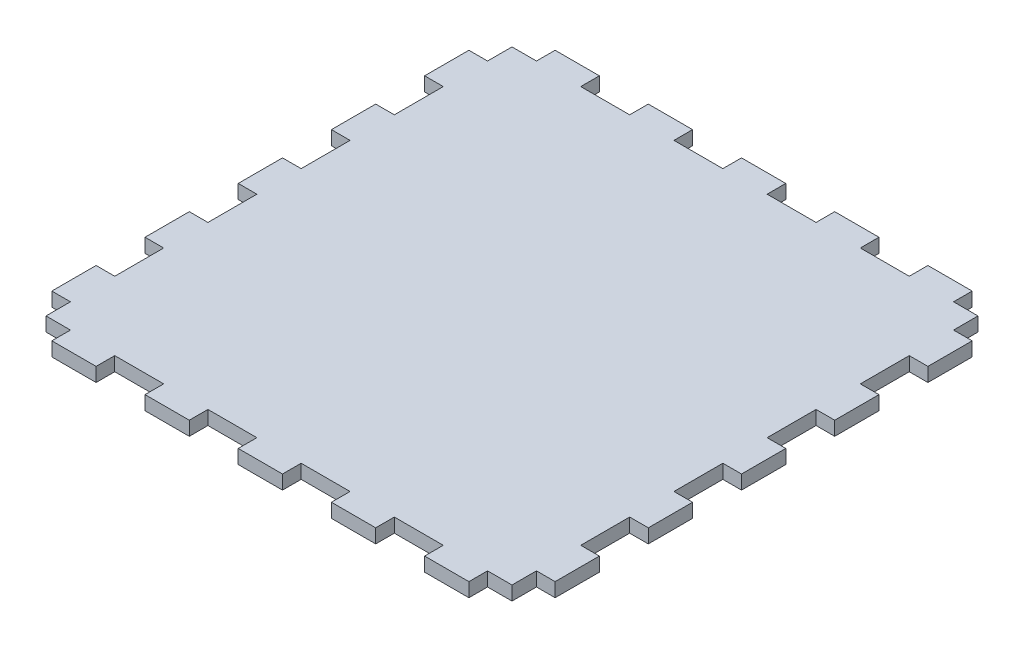
SolidWorks part; units mm, degrees
material "Teak"
ref_plane "Front Plane" through (0, 0, 0) normal (0, 0, 1) x (1, 0, 0)
ref_plane "Top Plane" through (0, 0, 0) normal (0, 1, 0) x (1, 0, 0)
ref_plane "Right Plane" through (0, 0, 0) normal (1, 0, 0) x (0, 0, -1)
sketch "Sketch2" plane through (0, 0, 0) normal (0, 1, 0) x (1, 0, 0)
  line L1 (-50, -50) -> (50, -50)
  line L2 (-50, -50) -> (-50, 50)
  line L3 (-50, 50) -> (50, 50)
  line L4 (50, -50) -> (50, 50)
  line L5 (-50, -50) -> (50, 50) construction
  line L6 (-50, 50) -> (50, -50) construction
  point P0 (0, 0)
  dimension "D1" = 100
  dimension "D2" = 100
extrude "Boss-Extrude1" add sketch "Sketch2" along normal blind 3
sketch "Sketch4" plane through (0, 0, 50) normal (0, 0, 1) x (1, 0, 0)
  line L0 (50, 1.5) -> (45, 1.5) construction
  line L1 (50, 3) -> (50, 0) construction
  line L2 (45, 1.5) -> (-45, 1.5) construction
  line L3 (-45, 1.5) -> (-50, 1.5) construction
  line L4 (-50, 3) -> (-50, 0) construction
  line L5 (-50, 3) -> (50, 3) construction
  line L6 (-35.25, 0) -> (-44.75, 0)
  line L7 (-35.25, 0) -> (-35.25, 3)
  line L8 (-35.25, 3) -> (-44.75, 3)
  line L9 (-44.75, 0) -> (-44.75, 3)
  line L10 (-35.25, 0) -> (-44.75, 3) construction
  line L11 (-35.25, 3) -> (-44.75, 0) construction
  line L12 (-25.25, 0) -> (-25.25, 3)
  line L13 (-25.25, 0) -> (-34.75, 0)
  line L14 (-34.75, 0) -> (-34.75, 3)
  line L15 (-25.25, 3) -> (-34.75, 3)
  line L16 (-15.25, 0) -> (-15.25, 3)
  line L17 (-15.25, 0) -> (-24.75, 0)
  line L18 (-24.75, 0) -> (-24.75, 3)
  line L19 (-15.25, 3) -> (-24.75, 3)
  line L20 (-5.25, 0) -> (-5.25, 3)
  line L21 (-5.25, 0) -> (-14.75, 0)
  line L22 (-14.75, 0) -> (-14.75, 3)
  line L23 (-5.25, 3) -> (-14.75, 3)
  line L24 (4.75, 0) -> (4.75, 3)
  line L25 (4.75, 0) -> (-4.75, 0)
  line L26 (-4.75, 0) -> (-4.75, 3)
  line L27 (4.75, 3) -> (-4.75, 3)
  line L28 (-35.25, 0) -> (-25.25, 0) construction
  line L29 (-15.25, 0) -> (-15.25, 3)
  line L30 (-15.25, 0) -> (-24.75, 0)
  line L31 (-24.75, 0) -> (-24.75, 3)
  line L32 (-15.25, 3) -> (-24.75, 3)
  line L33 (4.75, 0) -> (4.75, 3)
  line L34 (4.75, 0) -> (-4.75, 0)
  line L35 (-4.75, 0) -> (-4.75, 3)
  line L36 (4.75, 3) -> (-4.75, 3)
  line L37 (24.75, 0) -> (24.75, 3)
  line L38 (24.75, 0) -> (15.25, 0)
  line L39 (15.25, 0) -> (15.25, 3)
  line L40 (24.75, 3) -> (15.25, 3)
  line L41 (44.75, 0) -> (44.75, 3)
  line L42 (44.75, 0) -> (35.25, 0)
  line L43 (35.25, 0) -> (35.25, 3)
  line L44 (44.75, 3) -> (35.25, 3)
  line L45 (-35.25, 0) -> (-15.25, 0) construction
  point P8 (-40, 1.5)
  point P15 (0, 0)
  point P16 (-52.4687, 43.8595)
  point P53 (0, 0)
  line M6 (-50, 0) -> (50, 0)
  line M8 (50, 3) -> (-50, 3)
  dimension "D1" = 4.75
  dimension "D3" = 5
  dimension "D5" = 10
  dimension "D7" = 20
  dimension "D8" = 5
  dimension "D4" = 5
  dimension "D6" = 5
extrude "Boss-Extrude2" add sketch "Sketch4" along normal blind 4 contours L9 L7 M6 M8 | L16 L12 M6 M8 | L24 L20 M6 M8 | L39 L37 M6 M8 | L43 L41 M6 M8
sketch "Sketch5" plane through (-50, 0, 0) normal (-1, 0, 0) x (0, 0, 1)
  line L0 (50, 0) -> (50, 3) construction
  line L1 (54, 1.5) -> (50, 1.5) construction
  line L2 (54, 0) -> (54, 3) construction
  line L3 (50, 1.5) -> (-45, 1.5) construction
  line L4 (-45, 1.5) -> (-50, 1.5) construction
  line L5 (-50, 3) -> (-50, 0) construction
  line L6 (-50, 3) -> (50, 3) construction
  line L7 (-35.25, 0) -> (-44.75, 0)
  line L8 (-35.25, 0) -> (-35.25, 3)
  line L9 (-35.25, 3) -> (-44.75, 3)
  line L10 (-44.75, 0) -> (-44.75, 3)
  line L11 (-35.25, 0) -> (-44.75, 3) construction
  line L12 (-35.25, 3) -> (-44.75, 0) construction
  line L13 (-15.25, 0) -> (-15.25, 3)
  line L14 (-15.25, 0) -> (-24.75, 0)
  line L15 (-24.75, 0) -> (-24.75, 3)
  line L16 (-15.25, 3) -> (-24.75, 3)
  line L17 (-35.25, 0) -> (-15.25, 0) construction
  line L18 (-15.25, 0) -> (-15.25, 3)
  line L19 (-15.25, 0) -> (-24.75, 0)
  line L20 (-24.75, 0) -> (-24.75, 3)
  line L21 (-15.25, 3) -> (-24.75, 3)
  line L22 (4.75, 0) -> (4.75, 3)
  line L23 (4.75, 0) -> (-4.75, 0)
  line L24 (-4.75, 0) -> (-4.75, 3)
  line L25 (4.75, 3) -> (-4.75, 3)
  line L26 (24.75, 0) -> (24.75, 3)
  line L27 (24.75, 0) -> (15.25, 0)
  line L28 (15.25, 0) -> (15.25, 3)
  line L29 (24.75, 3) -> (15.25, 3)
  line L30 (44.75, 0) -> (44.75, 3)
  line L31 (44.75, 0) -> (35.25, 0)
  line L32 (35.25, 0) -> (35.25, 3)
  line L33 (44.75, 3) -> (35.25, 3)
  line L34 (-35.25, 0) -> (-15.25, 0) construction
  point P7 (-40, 1.5)
  dimension "D1" = 5
  dimension "D2" = 9.5
  dimension "D3" = 5
  dimension "D5" = 20
  dimension "D7" = 20
  dimension "D4" = 2
  dimension "D6" = 5
extrude "Boss-Extrude3" add sketch "Sketch5" along normal blind 4 contours L9 L10 L7 L8 | L14 L15 L16 L13 | L23 L24 L25 L22 | L27 L28 L29 L26 | L31 L32 L33 L30
sketch "Sketch6" plane through (50, 0, 0) normal (1, 0, 0) x (0, 0, -1)
  line L1 (45, 1.5) -> (-45, 1.5) construction
  line L3 (-45, 1.5) -> (-50, 1.5) construction
  line L4 (45, 1.5) -> (50, 1.5) construction
  line L5 (50, 3) -> (50, 0) construction
  line L7 (-50, 3) -> (-50, 0) construction
  line L8 (-50, 3) -> (50, 3) construction
  line L9 (-35.25, 0) -> (-44.75, 0)
  line L10 (-35.25, 0) -> (-35.25, 3)
  line L11 (-35.25, 3) -> (-44.75, 3)
  line L12 (-44.75, 0) -> (-44.75, 3)
  line L13 (-35.25, 0) -> (-44.75, 3) construction
  line L14 (-35.25, 3) -> (-44.75, 0) construction
  line L15 (-15.25, 0) -> (-15.25, 3)
  line L16 (-15.25, 0) -> (-24.75, 0)
  line L17 (-24.75, 0) -> (-24.75, 3)
  line L18 (-15.25, 3) -> (-24.75, 3)
  line L19 (4.75, 0) -> (4.75, 3)
  line L20 (4.75, 0) -> (-4.75, 0)
  line L21 (-4.75, 0) -> (-4.75, 3)
  line L22 (4.75, 3) -> (-4.75, 3)
  line L23 (24.75, 0) -> (24.75, 3)
  line L24 (24.75, 0) -> (15.25, 0)
  line L25 (15.25, 0) -> (15.25, 3)
  line L26 (24.75, 3) -> (15.25, 3)
  line L27 (44.75, 0) -> (44.75, 3)
  line L28 (44.75, 0) -> (35.25, 0)
  line L29 (35.25, 0) -> (35.25, 3)
  line L30 (44.75, 3) -> (35.25, 3)
  line L31 (-35.25, 0) -> (-15.25, 0) construction
  point P0 (-40, 1.5)
  dimension "D1" = 5
  dimension "D2" = 5
  dimension "D3" = 9.5
  dimension "D4" = 5
  dimension "D6" = 20
  dimension "D5" = 5
extrude "Boss-Extrude4" add sketch "Sketch6" along normal blind 4 contours L10 L9 L12 L11 | L15 L18 L17 L16 | L19 L22 L21 L20 | L23 L26 L25 L24 | L27 L30 L29 L28
sketch "Sketch7" plane through (0, 0, -50) normal (0, 0, -1) x (-1, 0, 0)
  line L0 (-50, 1.5) -> (-45, 1.5) construction
  line L1 (-50, 3) -> (-50, 0) construction
  line L2 (-45, 1.5) -> (45, 1.5) construction
  line L3 (45, 1.5) -> (50, 1.5) construction
  line L4 (50, 0) -> (50, 3) construction
  line L5 (-50, 3) -> (50, 3) construction
  line L6 (-35.25, 0) -> (-44.75, 0)
  line L7 (-35.25, 0) -> (-35.25, 3)
  line L8 (-35.25, 3) -> (-44.75, 3)
  line L9 (-44.75, 0) -> (-44.75, 3)
  line L10 (-35.25, 0) -> (-44.75, 3) construction
  line L11 (-35.25, 3) -> (-44.75, 0) construction
  line L12 (-15.25, 0) -> (-15.25, 3)
  line L13 (-15.25, 0) -> (-24.75, 0)
  line L14 (-24.75, 0) -> (-24.75, 3)
  line L15 (-15.25, 3) -> (-24.75, 3)
  line L16 (4.75, 0) -> (4.75, 3)
  line L17 (4.75, 0) -> (-4.75, 0)
  line L18 (-4.75, 0) -> (-4.75, 3)
  line L19 (4.75, 3) -> (-4.75, 3)
  line L20 (24.75, 0) -> (24.75, 3)
  line L21 (24.75, 0) -> (15.25, 0)
  line L22 (15.25, 0) -> (15.25, 3)
  line L23 (24.75, 3) -> (15.25, 3)
  line L24 (44.75, 0) -> (44.75, 3)
  line L25 (44.75, 0) -> (35.25, 0)
  line L26 (35.25, 0) -> (35.25, 3)
  line L27 (44.75, 3) -> (35.25, 3)
  line L28 (-35.25, 0) -> (-15.25, 0) construction
  point P5 (-40, 1.5)
  dimension "D1" = 5
  dimension "D2" = 90
  dimension "D3" = 9.5
  dimension "D4" = 5
  dimension "D6" = 20
  dimension "D5" = 5
extrude "Boss-Extrude5" add sketch "Sketch7" along normal blind 4
